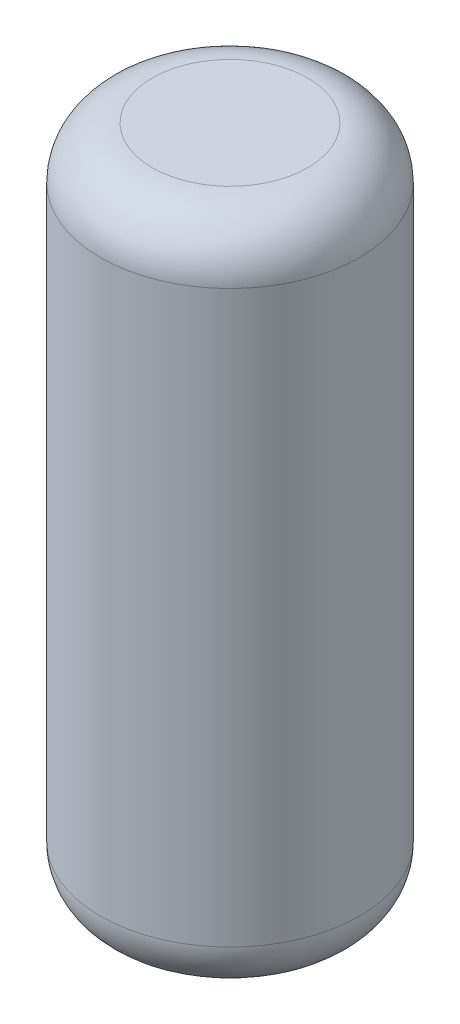
SolidWorks part; units mm, degrees
ref_plane "Front Plane" through (0, 0, 0) normal (0, 0, 1) x (1, 0, 0)
ref_plane "Top Plane" through (0, 0, 0) normal (0, 1, 0) x (1, 0, 0)
ref_plane "Right Plane" through (0, 0, 0) normal (1, 0, 0) x (0, 0, -1)
sketch "Sketch1" plane through (0, 0, 0) normal (0, 1, 0) x (1, 0, 0)
  circle A0 centre (0, 0) radius 2.5
  dimension "D1" = 5
extrude "Boss-Extrude1" add sketch "Sketch1" along normal blind 13
fillet "Fillet1" radius 1 2 edges at (0, 0, 2.5) (0, 13, 2.5)
